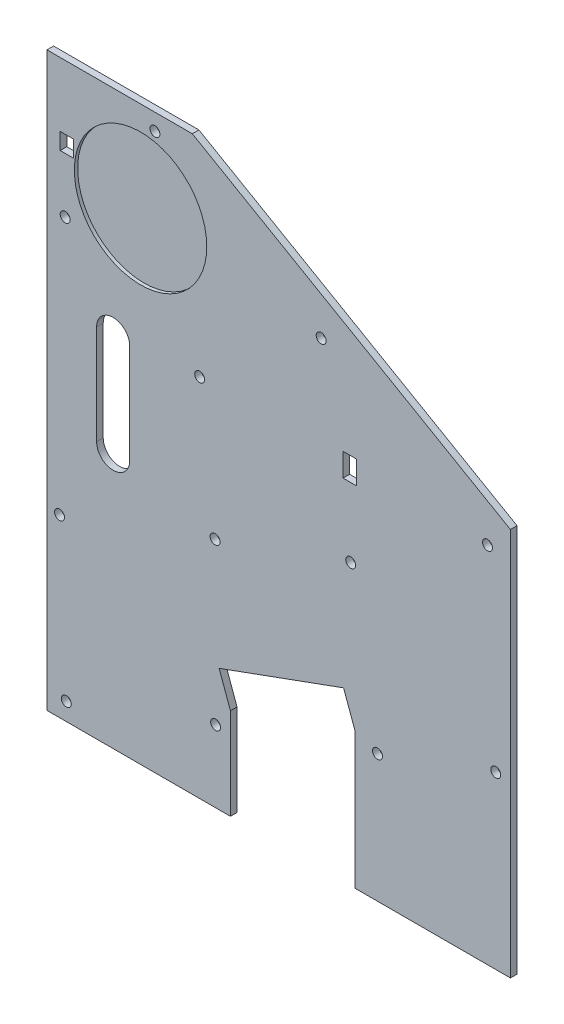
SolidWorks part; units mm, degrees
ref_plane "Front Plane" through (0, 0, 0) normal (0, 0, 1) x (1, 0, 0)
ref_plane "Top Plane" through (0, 0, 0) normal (0, 1, 0) x (1, 0, 0)
ref_plane "Right Plane" through (0, 0, 0) normal (1, 0, 0) x (0, 0, -1)
sketch "Sketch1" plane through (0, 0, 0) normal (0, 0, 1) x (1, 0, 0)
  line L19 (-70, 100) -> (-70, -72.7995) construction
  line L21 (70, -72.7995) -> (70, 44.5248) construction
  line L22 (-26.0859, 100) -> (70, 44.5248) construction
  line L23 (-26.0859, 100) -> (-70, 100) construction
  line L24 (-70, 100) -> (-70, -72.7995)
  line L25 (-70, -72.7995) -> (70, -72.7995)
  line L26 (70, -72.7995) -> (70, 44.5248)
  line L27 (-26.0859, 100) -> (70, 44.5248)
  line L28 (-26.0859, 100) -> (-70, 100)
extrude "Boss-Extrude1" add sketch "Sketch1" along normal blind 2
sketch "Sketch2" plane through (0, 0, 2) normal (0, 0, 1) x (1, 0, 0)
  line L5 (-26.0859, 100) -> (-70, 100)
  line L6 (-70, 100) -> (-70, -72.7995)
  line L7 (-70, -72.7995) -> (70, -72.7995)
  line L8 (70, -72.7995) -> (70, 44.5248)
  line L9 (70, 44.5248) -> (-26.0859, 100)
  line L10 (-26.0859, 100) -> (-70, 100)
  line L11 (-70, 100) -> (-70, -72.7995)
  line L12 (-70, -72.7995) -> (70, -72.7995)
  line L13 (70, -72.7995) -> (70, 44.5248)
  line L14 (70, 44.5248) -> (-26.0859, 100)
  circle A0 centre (-41.7237, 72.6554) radius 20
  dimension "D1" = 0
sketch "Sketch3" plane through (0, 0, 2) normal (0, 0, 1) x (1, 0, 0)
  line L0 (-17.9925, -35.7876) -> (19.5952, -22.1068)
  line L2 (19.5952, -22.1068) -> (23.0154, -31.5037)
  line L4 (-70, -65.3585) -> (-14.5723, -45.1845) construction
  line L5 (-66, 75.6554) -> (-62, 75.6554) construction
  line L6 (-66, 75.6554) -> (-62, 75.6554)
  line L7 (-66, 80.6554) -> (-66, 75.6554) construction
  line L8 (-66, 80.6554) -> (-62, 80.6554) construction
  line L9 (-62, 80.6554) -> (-62, 75.6554) construction
  line L10 (-26.0859, 100) -> (-70, 100)
  line L11 (-70, 100) -> (-70, -72.7995)
  line L12 (-70, -72.7995) -> (70, -72.7995)
  line L13 (70, -72.7995) -> (70, 44.5248)
  line L14 (70, 44.5248) -> (-26.0859, 100)
  line L15 (-26.0859, 100) -> (-70, 100)
  line L16 (-70, 100) -> (-70, -72.7995)
  line L17 (-70, -72.7995) -> (70, -72.7995)
  line L18 (70, -72.7995) -> (70, 44.5248)
  line L19 (70, 44.5248) -> (-26.0859, 100)
  line L20 (-66, 80.6554) -> (-66, 75.6554)
  line L21 (-66, 80.6554) -> (-62, 80.6554)
  line L22 (-62, 80.6554) -> (-62, 75.6554)
  line L23 (19.4272, 32.69) -> (23.4317, 32.69) construction
  line L24 (19.4272, 32.69) -> (19.4272, 39.6978) construction
  line L25 (23.4317, 32.69) -> (23.4317, 39.6978) construction
  line L26 (19.4272, 39.6978) -> (23.4317, 39.6978) construction
  line L27 (19.4272, 32.69) -> (23.4317, 32.69)
  line L28 (19.4272, 32.69) -> (19.4272, 39.6978)
  line L29 (23.4317, 32.69) -> (23.4317, 39.6978)
  line L30 (19.4272, 39.6978) -> (23.4317, 39.6978)
  line L31 (-17.9925, -35.7876) -> (-14.5723, -45.1845)
  line L32 (-14.5723, -45.1845) -> (-14.5723, -75.1845)
  line L33 (-14.5723, -75.1845) -> (23.0154, -75.1845)
  line L34 (23.0154, -75.1845) -> (23.0154, -31.5037)
  dimension "D1" = 10
  dimension "D2" = 30
  dimension "D3" = 0
extrude "Cut-Extrude1" cut sketch "Sketch3" against normal blind 10 contours L30 L28 L27 L29 | L22 L21 L20 L6 | L33 L34 L2 L0 L31 L32
sketch "Sketch4" plane through (0, 0, 2) normal (0, 0, 1) x (1, 0, 0)
  circle A0 centre (-41.7237, 72.6554) radius 20 construction
  circle A1 centre (-41.7237, 72.6554) radius 20
extrude "Cut-Extrude2" cut sketch "Sketch4" against normal blind 1
hole_wizard "Ø3.0mm Press Dowel Hole1" positions "Sketch5" profile "Sketch6" hole size "Ø3.0" standard "ANSI Metric"
sketch "Sketch5" plane through (-89.742, -119.4997, 0) normal (0, 0, -1) x (-1, 0, 0)
  point P0 (-23.5423, 99.781)
  point P1 (-25.5944, 52.0145)
  point P2 (-70.6996, 68.4315)
  point P3 (-70.5269, 116.8821)
  point P4 (-111.4918, 131.26)
  point P5 (-119.5864, 85.3143)
  point P6 (-155.2948, 98.311)
  point P7 (-152.8064, 156.4818)
  point P8 (-65.8782, 157.0177)
  point P9 (-102.577, 185.4818)
  point P10 (-52.3475, 214.4818)
  point P11 (-25.242, 178.4997)
  point P24 (0, 0)
sketch "Sketch6" plane through (-66.1998, -19.7187, 0) normal (1, 0, 0) x (0, 1, 0)
  line L0 (0, 0) -> (0, 1.999)
  line L1 (0, 1.999) -> (1.5, 1.999)
  line L2 (1.5, 1.999) -> (1.5, 0)
  line L3 (1.5, 0) -> (0, 0)
  line L4 (0, -6.35) -> (0, 107.95) construction
  dimension "Thru Hole Dia." = 3
  dimension "Thru Hole Depth" = 1.999
extrude "Cut-Extrude3" cut sketch "Sketch7" against normal through all
sketch "Sketch7" plane through (-89.742, -119.4997, 2) normal (0, 0, 1) x (1, 0, 0)
  line L0 (39.742, 154.4997) -> (39.742, 124.4997) construction
  line L1 (44.742, 154.4997) -> (44.742, 124.4997)
  line L2 (34.742, 154.4997) -> (34.742, 124.4997)
  arc A0 (44.742, 154.4997) -> (34.742, 154.4997) centre (39.742, 154.4997) ccw
  arc A1 (34.742, 124.4997) -> (44.742, 124.4997) centre (39.742, 124.4997) ccw
  point P2 (39.742, 139.4997)
  point P9 (0, 0)
